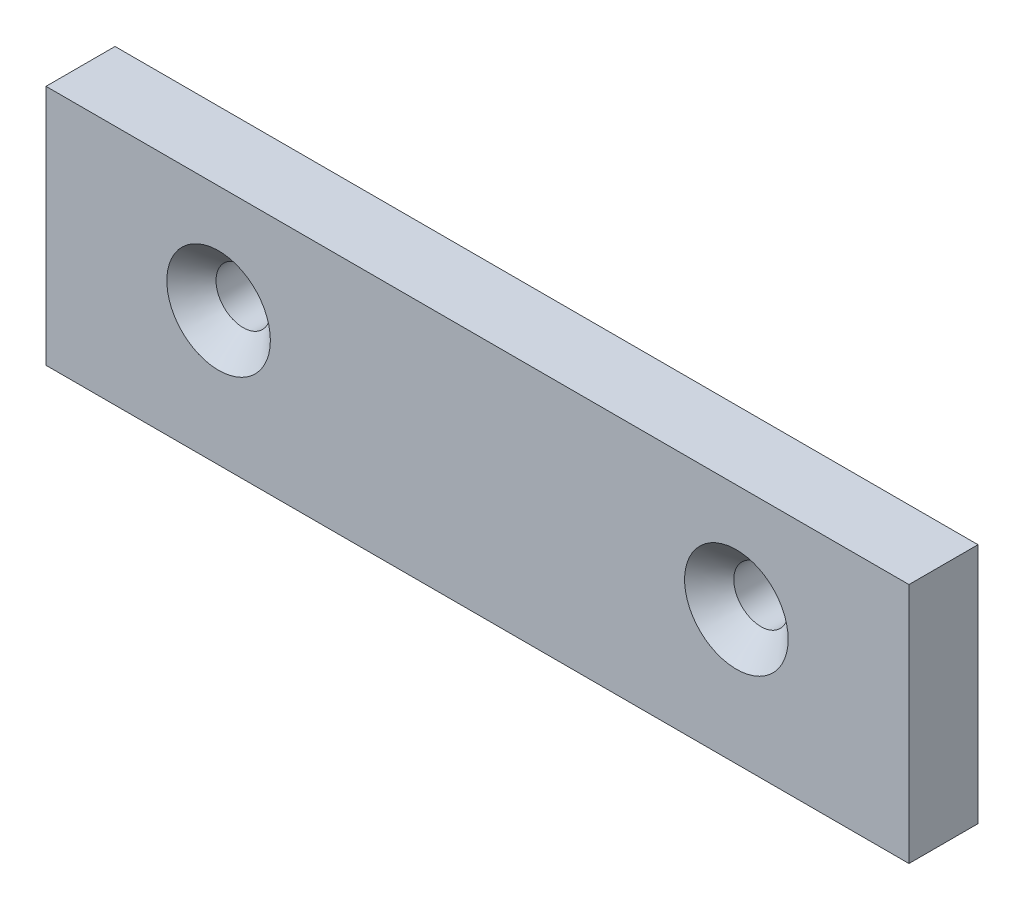
SolidWorks part; units mm, degrees
material "201 Annealed Stainless Steel (SS)"
ref_plane "Front Plane" through (0, 0, 0) normal (0, 0, 1) x (1, 0, 0)
ref_plane "Top Plane" through (0, 0, 0) normal (0, 1, 0) x (1, 0, 0)
ref_plane "Right Plane" through (0, 0, 0) normal (1, 0, 0) x (0, 0, -1)
sketch "Sketch1" plane through (0, 0, 0) normal (0, 0, 1) x (1, 0, 0)
  line L1 (-50, -14) -> (50, -14)
  line L2 (-50, -14) -> (-50, 14)
  line L3 (-50, 14) -> (50, 14)
  line L4 (50, -14) -> (50, 14)
  line L5 (-50, -14) -> (50, 14) construction
  line L6 (-50, 14) -> (50, -14) construction
  point P0 (0, 0)
  dimension "D1" = 100
  dimension "D2" = 28
extrude "Boss-Extrude1" add sketch "Sketch1" along normal blind 8
sketch "Sketch2" plane through (0, 0, 8) normal (0, 0, 1) x (1, 0, 0)
  line L0 (50, -14) -> (50, 14) construction
  line L2 (50, 14) -> (-50, 14) construction
  point P0 (-30, 1.5)
  point P1 (30, 1.5)
  dimension "D1" = 60
  dimension "D2" = 20
  dimension "D3" = 12.5
hole_wizard "Hole1" positions "3DSketch1" profile "Sketch3" legacy
sketch3d "3DSketch1"
  point P0 (-30, 1.5, 8)
  point P3 (30, 1.5, 8)
  point P6 (-30, 1.5, 8)
sketch "Sketch3" plane through (-30, 1.5, 8) normal (1, 0, 0) x (0, -1, 0)
  line L0 (0, 0) -> (0, 50)
  line L1 (0, 50) -> (3.15, 50)
  line L2 (3.15, 50) -> (3.15, 2.85)
  line L3 (3.15, 2.85) -> (6, 0)
  line L4 (6, 0) -> (0, 0)
  line L5 (0, -6.4453) -> (0, 115.525) construction
  line L6 (-3.15, 2.85) -> (-6, 0) construction
  dimension "Diameter" = 6.3
  dimension "Depth" = 50
  dimension "C-Sink Angle" = 90
  dimension "C-Sink Diameter" = 12
